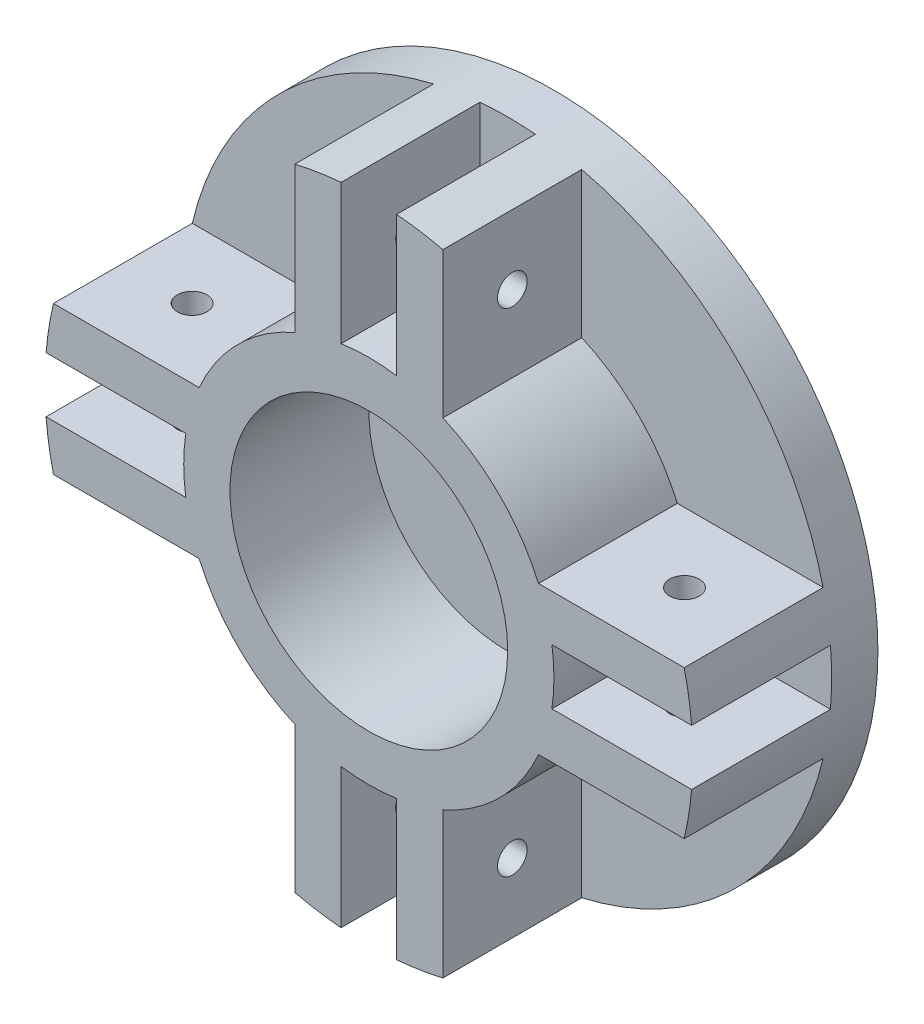
SolidWorks part; units mm, degrees
ref_plane "Front Plane" through (0, 0, 0) normal (0, 0, 1) x (1, 0, 0)
ref_plane "Top Plane" through (0, 0, 0) normal (0, 1, 0) x (1, 0, 0)
ref_plane "Right Plane" through (0, 0, 0) normal (1, 0, 0) x (0, 0, -1)
sketch "Sketch2" plane through (0, 0, 0) normal (0, 0, 1) x (1, 0, 0)
  circle A0 centre (0, 0) radius 5
  circle A1 centre (0, 0) radius 35
  dimension "D1" = 10
  dimension "D2" = 30
extrude "Boss-Extrude1" add sketch "Sketch2" along normal blind 5
sketch "Sketch3" plane through (0, 0, 5) normal (0, 0, 1) x (1, 0, 0)
  line L0 (0, 20) -> (0, 35) construction
  line L1 (3, 19.7737) -> (3, 34.8712)
  line L2 (-3, 19.7737) -> (3, 19.7737) construction
  line L3 (8, 18.3303) -> (8, 34.0735)
  line L4 (-8, 18.3303) -> (-8, 34.0735)
  line L5 (-3, 19.7737) -> (-3, 34.8712)
  line L6 (18.3303, 8) -> (34.0735, 8)
  line L7 (19.7737, 3) -> (34.8712, 3)
  line L8 (19.7737, -3) -> (34.8712, -3)
  line L9 (18.3303, -8) -> (34.0735, -8)
  line L10 (8, -18.3303) -> (8, -34.0735)
  line L11 (3, -19.7737) -> (3, -34.8712)
  line L12 (-3, -19.7737) -> (-3, -34.8712)
  line L13 (-8, -18.3303) -> (-8, -34.0735)
  line L14 (-18.3303, -8) -> (-34.0735, -8)
  line L15 (-19.7737, -3) -> (-34.8712, -3)
  line L16 (-19.7737, 3) -> (-34.8712, 3)
  line L17 (-18.3303, 8) -> (-34.0735, 8)
  circle A0 centre (0, 0) radius 15
  circle A1 centre (0, 0) radius 20
  circle A2 centre (0, 0) radius 35 construction
  arc A3 (3, 34.8712) -> (8, 34.0735) centre (0, 0) cw
  arc A4 (3, 19.7737) -> (8, 18.3303) centre (0, 0) cw
  arc A5 (-3, 34.8712) -> (-8, 34.0735) centre (0, 0) ccw
  arc A6 (-3, 19.7737) -> (-8, 18.3303) centre (0, 0) ccw
  arc A7 (34.8712, 3) -> (34.0735, 8) centre (0, 0) ccw
  arc A8 (34.8712, -3) -> (34.0735, -8) centre (0, 0) cw
  arc A9 (3, -34.8712) -> (8, -34.0735) centre (0, 0) ccw
  arc A10 (-3, -34.8712) -> (-8, -34.0735) centre (0, 0) cw
  arc A11 (-34.8712, -3) -> (-34.0735, -8) centre (0, 0) ccw
  arc A12 (-34.8712, 3) -> (-34.0735, 8) centre (0, 0) cw
  point P11 (0, 19.7737)
  point P26 (0, 0)
  point P49 (0, 0)
  circle M4 centre (0, 0) radius 35
  dimension "D5" = 30
  dimension "D2" = 5
  dimension "D3" = 3
  dimension "D1" = 5
  dimension "D4" = 4
extrude "Boss-Extrude3" add sketch "Sketch3" along normal blind 15 contours A1 L13 L12 M4 | A1 L11 L10 M4 | A1 L9 L8 M4 | A1 L7 L6 M4 | A1 L3 L1 M4 | A1 L5 L4 M4 | A1 L17 L16 M4 | A1 L15 L14 M4 | A1 A0
sketch "Sketch4" plane through (-8, 0, 0) normal (-1, 0, 0) x (0, 0, 1)
  circle A0 centre (12.5, 26.5963) radius 1.6
  dimension "D1" = 3.2
extrude "Cut-Extrude1" cut sketch "Sketch4" against normal through all
pattern_circular "CirPattern1" count 4 over 360 about axis through (0, 0, 20) along (0, 0, -1) of "Cut-Extrude1"
